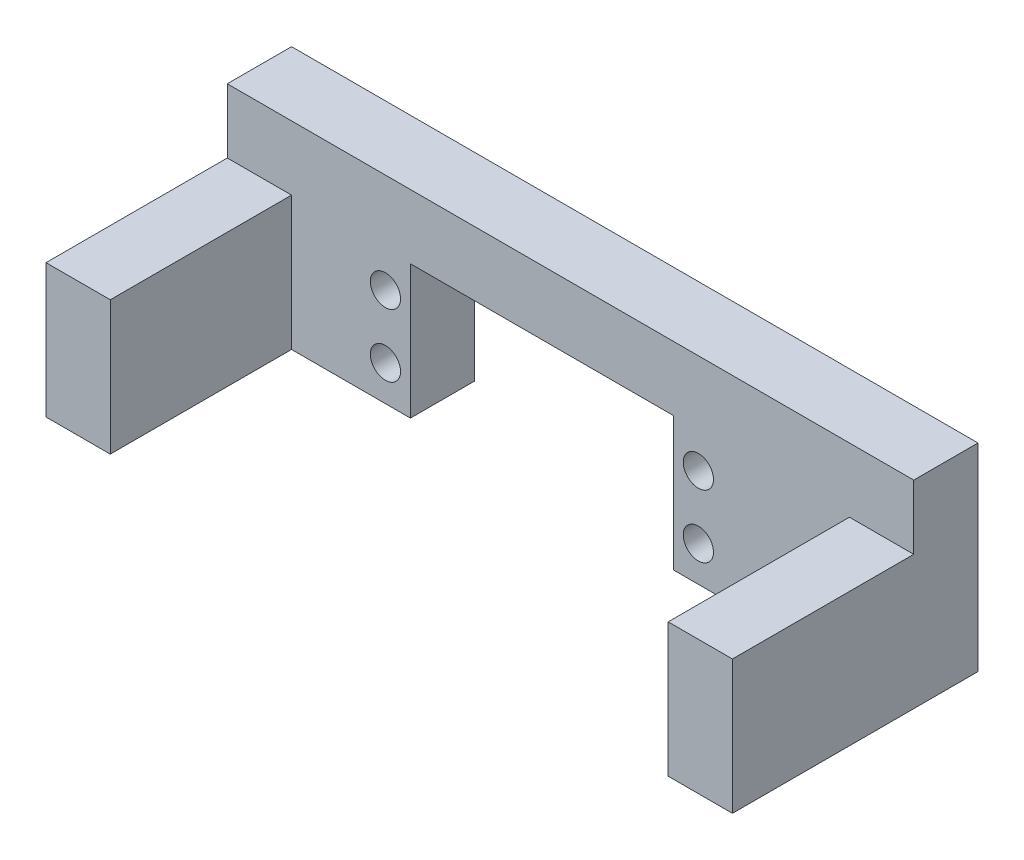
SolidWorks part; units mm, degrees
ref_plane "Front Plane" through (0, 0, 0) normal (0, 0, 1) x (1, 0, 0)
ref_plane "Top Plane" through (0, 0, 0) normal (0, 1, 0) x (1, 0, 0)
ref_plane "Right Plane" through (0, 0, 0) normal (1, 0, 0) x (0, 0, -1)
sketch "Sketch1" plane through (0, 0, 0) normal (0, 0, 1) x (1, 0, 0)
  line L1 (-48.395, 10.4) -> (48.395, 10.4) construction
  line L2 (-48.395, 10.4) -> (-48.395, -10.4) construction
  line L3 (-48.395, -10.4) -> (48.395, -10.4) construction
  line L4 (48.395, 10.4) -> (48.395, -10.4) construction
  line L5 (-48.395, 10.4) -> (48.395, -10.4) construction
  line L6 (-48.395, -10.4) -> (48.395, 10.4) construction
  line L7 (-48.395, -10.4) -> (-29.9, -10.4)
  line L8 (-48.395, -10.4) -> (-48.395, 10.4)
  line L9 (-48.395, 10.4) -> (-29.9, 10.4)
  line L10 (-29.9, -10.4) -> (-29.9, 10.4)
  line L11 (-48.395, -10.4) -> (-29.9, 10.4) construction
  line L12 (-48.395, 10.4) -> (-29.9, -10.4) construction
  line L13 (48.395, 10.4) -> (11, 10.4)
  line L14 (48.395, 10.4) -> (48.395, -10.4)
  line L15 (48.395, -10.4) -> (11, -10.4)
  line L16 (11, 10.4) -> (11, -10.4)
  line L17 (48.395, 10.4) -> (11, -10.4) construction
  line L18 (48.395, -10.4) -> (11, 10.4) construction
  line L19 (-48.395, 10.4) -> (-58.395, 10.4)
  line L20 (-48.395, 10.4) -> (-48.395, -10.4)
  line L21 (-48.395, -10.4) -> (-58.395, -10.4)
  line L22 (-58.395, 10.4) -> (-58.395, -10.4)
  line L23 (-48.395, 10.4) -> (-58.395, -10.4) construction
  line L24 (-48.395, -10.4) -> (-58.395, 10.4) construction
  point P0 (0, 0)
  point P8 (-39.1475, 0)
  point P11 (29.6975, 0)
  point P14 (-53.395, 0)
  dimension "D1" = 96.79
  dimension "D2" = 20.8
  dimension "D3" = 18.495
  dimension "D4" = 37.395
  dimension "D5" = 10
extrude "Boss-Extrude1" add sketch "Sketch1" along normal blind 10 contours L2 L1 L4 L3 | L8 L7 L10 L9 | L14 L13 L16 L15 | L20 L19 L22 L21
sketch "Sketch2" plane through (0, 0, 10) normal (0, 0, 1) x (1, 0, 0)
  line L0 (-29.9, -10.4) -> (-58.395, -10.4) construction
  line L7 (48.395, -10.4) -> (11, -10.4) construction
  line L8 (48.395, 10.4) -> (38.395, 10.4)
  line L9 (48.395, 10.4) -> (48.395, -10.4)
  line L10 (48.395, -10.4) -> (38.395, -10.4)
  line L11 (38.395, 10.4) -> (38.395, -10.4)
  line L12 (48.395, 10.4) -> (38.395, -10.4) construction
  line L13 (48.395, -10.4) -> (38.395, 10.4) construction
  line L17 (-58.395, 10.4) -> (-48.395, 10.4)
  line L18 (-58.395, 10.4) -> (-58.395, -10.4)
  line L19 (-58.395, -10.4) -> (-48.395, -10.4)
  line L20 (-48.395, 10.4) -> (-48.395, -10.4)
  line L21 (-58.395, 10.4) -> (-48.395, -10.4) construction
  line L22 (-58.395, -10.4) -> (-48.395, 10.4) construction
  point P4 (-53.395, 0)
  point P12 (43.395, 0)
  dimension "D1" = 10
  dimension "D2" = 10
extrude "Boss-Extrude2" add sketch "Sketch2" along normal blind 28.2
sketch "Sketch3" plane through (0, -10.4, 0) normal (0, -1, 0) x (1, 0, 0)
sketch "Sketch6" plane through (0, 10.4, 0) normal (0, 1, 0) x (1, 0, 0)
  line L5 (48.395, -38.2) -> (48.395, 0) construction
  line L6 (-58.395, 0) -> (48.395, 0)
  line L7 (-58.395, 0) -> (-58.395, -10)
  line L8 (-58.395, -10) -> (48.395, -10)
  line L9 (48.395, 0) -> (48.395, -10)
  line L10 (-58.395, 0) -> (48.395, -10) construction
  line L11 (-58.395, -10) -> (48.395, 0) construction
  point P4 (-5, -5)
  dimension "D1" = 10
extrude "Boss-Extrude4" add sketch "Sketch6" along normal blind 10
sketch "Sketch9" plane through (0, 0, 10) normal (0, 0, 1) x (1, 0, 0)
  line L0 (11, 10.4) -> (-29.9, 10.4) construction
  line L1 (-9.45, 10.4) -> (-9.45, -6.4957) construction
  line L2 (11, 10.4) -> (11, -10.4) construction
  line L3 (11, 0) -> (14.89, 0) construction
  line L4 (14.89, 0) -> (14.89, -4.9) construction
  circle A0 centre (14.89, -4.9) radius 2.35
  circle A1 centre (14.89, 4.9) radius 2.35
  circle A2 centre (-33.79, -4.9) radius 2.35
  circle A3 centre (-33.79, 4.9) radius 2.35
  dimension "D3" = 4.7
  dimension "D1" = 3.89
  dimension "D2" = 4.9
extrude "Cut-Extrude1" cut sketch "Sketch9" against normal blind 10
